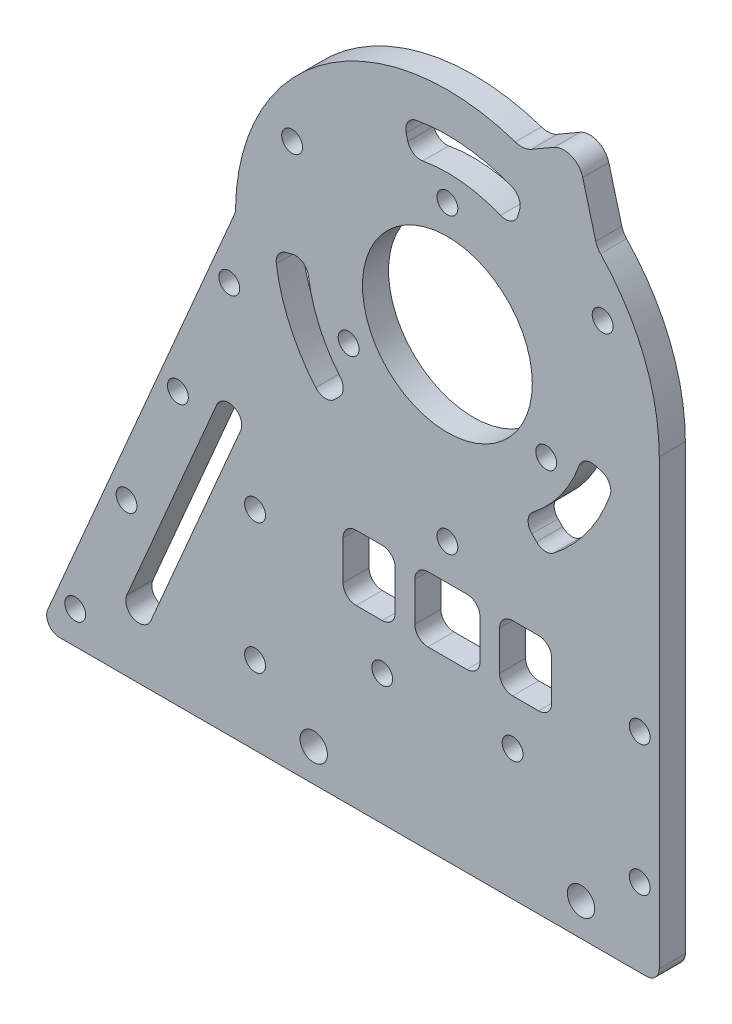
SolidWorks part; units mm, degrees
material "6061 合金"
ref_plane "前视" through (0, 0, 0) normal (0, 0, 1) x (1, 0, 0)
ref_plane "上视" through (0, 0, 0) normal (0, 1, 0) x (1, 0, 0)
ref_plane "右视" through (0, 0, 0) normal (1, 0, 0) x (0, 0, -1)
sketch "草图1" plane through (0, 0, 0) normal (0, 0, 1) x (1, 0, 0)
  circle A0 centre (0, 0) radius 32.5
  circle A1 centre (0, 0) radius 13.025
  dimension "D1" = 26.05
  dimension "D2" = 65
extrude "凸台-拉伸1" add sketch "草图1" along normal blind 4
sketch "草图2" plane through (0, 0, 4) normal (0, 0, 1) x (1, 0, 0)
  line L0 (-32.5, 0) -> (-32.5, -70)
  line L1 (-32.5, -70) -> (32.5, -70)
  line L2 (32.5, -70) -> (32.5, 0)
  circle A0 centre (0, 0) radius 32.5 construction
  arc A1 (-32.5, 0) -> (32.5, 0) centre (0, 0) ccw
  dimension "D1" = 70
extrude "凸台-拉伸2" add sketch "草图2" against normal blind 4
sketch "草图4" plane through (0, 0, 4) normal (0, 0, 1) x (1, 0, 0)
  line L0 (0, 0) -> (0, 32.5) construction
  arc A0 (32.5, 0) -> (-32.5, 0) centre (0, 0) ccw construction
  circle A1 centre (0, 17.5) radius 1.6
  circle A2 centre (15.1554, -8.75) radius 1.6
  circle A3 centre (-15.1554, -8.75) radius 1.6
  point P14 (0, 0)
  dimension "D1" = 3.2
  dimension "D2" = 17.5
  dimension "D3" = 3
extrude "切除-拉伸1" cut sketch "草图4" against normal blind 4
sketch "草图5" plane through (0, 0, 4) normal (0, 0, 1) x (1, 0, 0)
  line L0 (-20.5, -65) -> (20.5, -65) construction
  line L1 (-32.5, -70) -> (32.5, -70) construction
  line L2 (0, 0) -> (0, -70) construction
  line L4 (-32.5, -70) -> (32.5, -70) construction
  circle A0 centre (-20.5, -65) radius 2.1
  circle A1 centre (20.5, -65) radius 2.1
  dimension "D1" = 4.2
  dimension "D2" = 41
  dimension "D3" = 5
extrude "切除-拉伸2" cut sketch "草图5" against normal blind 4
sketch "草图6" plane through (0, 0, 0) normal (0, 0, -1) x (-1, 0, 0)
  line L0 (32.5, -70) -> (-32.5, -70) construction
  line L1 (0, 0) -> (0, -70) construction
  line L3 (32.5, -70) -> (-32.5, -70) construction
  circle A0 centre (-10, -50) radius 1.6
  circle A1 centre (10, -50) radius 1.6
  dimension "D1" = 3.2
  dimension "D2" = 20
  dimension "D3" = 20
extrude "切除-拉伸3" cut sketch "草图6" against normal blind 10
sketch "草图7" plane through (0, 0, 0) normal (0, 0, -1) x (-1, 0, 0)
  line L0 (32.5, -70) -> (-32.5, -70) construction
  line L3 (32.5, -70) -> (-32.5, -70) construction
  line L10 (5, -33) -> (-5, -33)
  line L11 (5, -33) -> (5, -43)
  line L17 (5, -43) -> (-5, -43)
  line L18 (-5, -33) -> (-5, -43)
  line L22 (5, -33) -> (-5, -43) construction
  line L23 (5, -43) -> (-5, -33) construction
  line L24 (0, 0) -> (0, -70) construction
  line L26 (-16, -43) -> (-8, -33) construction
  line L27 (16, -33) -> (8, -33)
  line L28 (16, -33) -> (16, -43)
  line L29 (16, -43) -> (8, -43)
  line L30 (8, -33) -> (8, -43)
  line L31 (16, -33) -> (8, -43) construction
  line L32 (16, -43) -> (8, -33) construction
  line L33 (-16, -33) -> (-8, -43) construction
  line L34 (-8, -33) -> (-8, -43)
  line L35 (-16, -43) -> (-8, -43)
  line L36 (-16, -33) -> (-16, -43)
  line L37 (-16, -33) -> (-8, -33)
  point P10 (0, -38)
  point P24 (12, -38)
  point P31 (-12, -38)
  dimension "D3" = 10
  dimension "D4" = 10
  dimension "D5" = 27
  dimension "D6" = 8
  dimension "D7" = 3
extrude "切除-拉伸4" cut sketch "草图7" against normal blind 10
fillet "圆角2" radius 2 13 edges at (32.5, -70, 2) (16, -33, 2) (8, -43, 2) (16, -43, 2) (8, -33, 2) (5, -33, 2) (-5, -43, 2) (5, -43, 2) (-5, -33, 2) (-8, -33, 2) (-16, -43, 2) (-8, -43, 2) (-16, -33, 2)
sketch "草图8" plane through (0, 0, 4) normal (0, 0, 1) x (1, 0, 0)
  line L0 (29.5, -70) -> (29.5, 21.3994) construction
  line L1 (-32.5, -70) -> (30.5, -70) construction
  line L2 (32.5, -68) -> (32.5, 0) construction
  line L3 (0, 40.1346) -> (0, -97.6524) construction
  line L4 (-29.5, -70) -> (-29.5, 21.3994) construction
  circle A0 centre (29.5, -58) radius 1.6
  circle A1 centre (29.5, -38) radius 1.6
  circle A2 centre (-29.5, -38) radius 1.6
  circle A3 centre (-29.5, -58) radius 1.6
  dimension "D2" = 3.2
  dimension "D3" = 20
  dimension "D4" = 12
  dimension "D1" = 3
extrude "切除-拉伸5" cut sketch "草图8" against normal blind 10
sketch "草图9" plane through (0, 0, 4) normal (0, 0, 1) x (1, 0, 0)
  line L0 (11.6653, 30.3343) -> (19.7465, 35)
  line L2 (22.9619, 23) -> (19.7465, 35)
  line L3 (0, 0) -> (39.2863, 0) construction
  arc A0 (32.5, 0) -> (-32.5, 0) centre (0, 0) ccw construction
  arc A1 (22.9619, 23) -> (11.6653, 30.3343) centre (0, 0) ccw
  circle A2 centre (0, 0) radius 13.025 construction
  dimension "D1" = 35
  dimension "D2" = 12
  dimension "D3" = 105
  dimension "D4" = 30
extrude "凸台-拉伸4" add sketch "草图9" against normal blind 4
fillet "圆角3" radius 3 3 edges at (22.9619, 23, 2) (19.7465, 35, 2) (11.6653, 30.3343, 2)
sketch "草图11" plane through (0, 0, 0) normal (0, 0, -1) x (-1, 0, 0)
  line L0 (32.5, 0) -> (62.5, -70)
  line L1 (32.5, 0) -> (32.5, -70) construction
  line L2 (62.5, -70) -> (32.5, -70)
  line L3 (32.5, -70) -> (32.5, 0)
  line L4 (32.5, -70) -> (-30.5, -70) construction
  arc A0 (32.5, 0) -> (-10.4112, 30.7873) centre (0, 0) ccw construction
  dimension "D1" = 30
extrude "凸台-拉伸5" add sketch "草图11" against normal blind 4
fillet "圆角4" radius 2 2 edges at (-62.5, -70, 2) (-32.5, 0, 2)
sketch "草图12" plane through (0, 0, 0) normal (0, 0, -1) x (-1, 0, 0)
  line L0 (-10.2176, 18.9169) -> (-11.5408, 23.855)
  line L1 (5.5646, 20.7674) -> (6.8587, 25.597)
  line L2 (0, 21.5) -> (0, 35.6311) construction
  line L3 (21.4914, -0.6097) -> (26.4294, -1.9329)
  line L4 (15.2028, -15.2028) -> (18.7383, -18.7383)
  line L5 (-11.2737, -18.3072) -> (-14.8886, -21.9221)
  line L6 (-20.7674, -5.5646) -> (-25.597, -6.8587)
  arc A0 (5.5646, 20.7674) -> (-10.2176, 18.9169) centre (0, 0) ccw
  arc A1 (6.8587, 25.597) -> (-11.5408, 23.855) centre (0, 0) ccw
  arc A2 (15.2028, -15.2028) -> (21.4914, -0.6097) centre (0, 0) ccw
  arc A3 (18.7383, -18.7383) -> (26.4294, -1.9329) centre (0, 0) ccw
  arc A4 (-20.7674, -5.5646) -> (-11.2737, -18.3072) centre (0, 0) ccw
  arc A5 (-25.597, -6.8587) -> (-14.8886, -21.9221) centre (0, 0) ccw
  point P30 (0, 0)
  dimension "D3" = 43
  dimension "D4" = 53
  dimension "D1" = 30
  dimension "D2" = 15
  dimension "D5" = 3
extrude "切除-拉伸6" cut sketch "草图12" against normal blind 17
fillet "圆角5" radius 2 12 edges at (11.2737, -18.3072, 2) (14.8886, -21.9221, 2) (20.7674, -5.5646, 2) (-21.4914, -0.6097, 2) (-26.4294, -1.9329, 2) (-18.7383, -18.7383, 2) (-15.2028, -15.2028, 2) (25.597, -6.8587, 2) (10.2176, 18.9169, 2) (-6.8587, 25.597, 2) (-5.5646, 20.7674, 2) (11.5408, 23.855, 2)
sketch "草图14" plane through (0, 0, 0) normal (0, 0, -1) x (-1, 0, 0)
  line L0 (33.5474, -27.8299) -> (47.3346, -60) construction
  line L1 (35.3857, -27.0421) -> (49.1729, -59.2122)
  line L2 (31.7091, -28.6178) -> (45.4963, -60.7878)
  line L3 (61.3052, -67.2122) -> (32.6592, -0.3715) construction
  line L4 (59.4669, -70) -> (-30.5, -70) construction
  line L5 (36.5886, -17.1557) -> (56.0397, -62.5417) construction
  arc A0 (35.3857, -27.0421) -> (31.7091, -28.6178) centre (33.5474, -27.8299) ccw
  arc A1 (45.4963, -60.7878) -> (49.1729, -59.2122) centre (47.3346, -60) ccw
  circle A2 centre (33.4581, -9.8513) radius 1.6
  circle A3 centre (41.3365, -28.2342) radius 1.6
  circle A4 centre (49.2149, -46.6171) radius 1.6
  circle A5 centre (57.0932, -65) radius 1.6
  point P2 (40.441, -43.915)
  dimension "D1" = 2
  dimension "D6" = 3.2
  dimension "D7" = 20
  dimension "D8" = 20
  dimension "D9" = 5
  dimension "D10" = 20
  dimension "D2" = 8
  dimension "D3" = 10
  dimension "D4" = 35
  dimension "D5" = 3
extrude "切除-拉伸7" cut sketch "草图14" against normal blind 17
sketch "草图15" plane through (0, 0, 0) normal (0, 0, -1) x (-1, 0, 0)
  circle A0 centre (0, 0) radius 27.5 construction
  circle A1 centre (0, -27.5) radius 1.6
  circle A2 centre (-23.8157, 13.75) radius 1.6
  circle A3 centre (23.8157, 13.75) radius 1.6
  point P11 (0, 0)
  dimension "D1" = 55
  dimension "D2" = 3.2
  dimension "D3" = 3
extrude "切除-拉伸8" cut sketch "草图15" against normal blind 10
